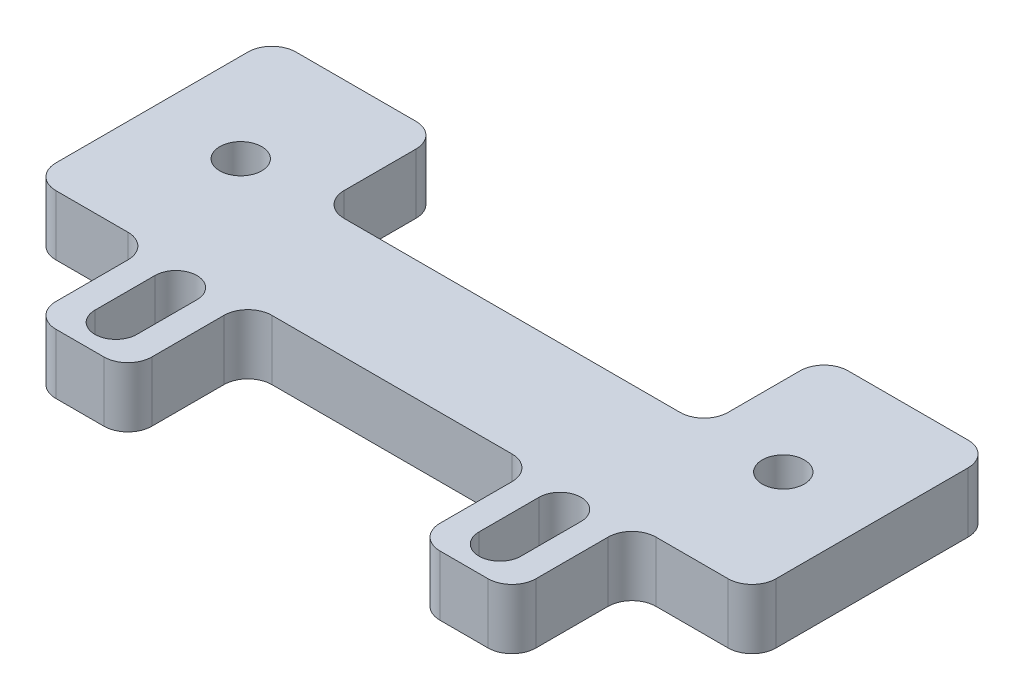
SolidWorks part; units mm, degrees
ref_plane "Front Plane" through (0, 0, 0) normal (0, 0, 1) x (1, 0, 0)
ref_plane "Top Plane" through (0, 0, 0) normal (0, 1, 0) x (1, 0, 0)
ref_plane "Right Plane" through (0, 0, 0) normal (1, 0, 0) x (0, 0, -1)
sketch "Sketch1" plane through (0, 0, 0) normal (0, 1, 0) x (1, 0, 0)
  line L0 (-38.1, 0) -> (-20.32, 0)
  line L1 (-38.1, 0) -> (-38.1, -25.4)
  line L2 (-38.1, -25.4) -> (-25.4, -25.4)
  line L3 (38.1, -25.4) -> (38.1, 0)
  line L4 (-38.1, -12.7) -> (38.1, -12.7) construction
  line L5 (0, -12.7) -> (0, -63.5) construction
  line L6 (-25.4, -25.4) -> (-25.4, -38.1)
  line L7 (-25.4, -38.1) -> (-15.24, -38.1)
  line L8 (25.4, -38.1) -> (25.4, -25.4)
  line L9 (25.4, -25.4) -> (38.1, -25.4)
  line L10 (-20.32, -38.1) -> (-20.32, 0) construction
  line L11 (20.32, -38.1) -> (20.32, 0) construction
  line L12 (-20.32, -27.94) -> (-20.32, -34.29) construction
  line L13 (-18.0975, -27.94) -> (-18.0975, -34.29)
  line L14 (-22.5425, -27.94) -> (-22.5425, -34.29)
  line L15 (20.32, -27.94) -> (20.32, -34.29) construction
  line L16 (18.0975, -27.94) -> (18.0975, -34.29)
  line L17 (22.5425, -27.94) -> (22.5425, -34.29)
  line L18 (-15.24, -38.1) -> (-15.24, -25.4)
  line L19 (-15.24, -25.4) -> (15.24, -25.4)
  line L20 (15.24, -25.4) -> (15.24, -38.1)
  line L21 (15.24, -38.1) -> (25.4, -38.1)
  line L22 (-20.32, 0) -> (-20.32, -12.7)
  line L23 (-20.32, -12.7) -> (20.32, -12.7)
  line L24 (20.32, -12.7) -> (20.32, 0)
  line L25 (20.32, 0) -> (38.1, 0)
  circle A0 centre (-28.702, -12.7) radius 2.2225
  circle A1 centre (28.702, -12.7) radius 2.2225
  arc A2 (-18.0975, -27.94) -> (-22.5425, -27.94) centre (-20.32, -27.94) ccw
  arc A3 (-22.5425, -34.29) -> (-18.0975, -34.29) centre (-20.32, -34.29) ccw
  arc A4 (18.0975, -27.94) -> (22.5425, -27.94) centre (20.32, -27.94) cw
  arc A5 (22.5425, -34.29) -> (18.0975, -34.29) centre (20.32, -34.29) cw
  point P4 (0, 0)
  point P24 (-20.32, -31.115)
  point P31 (20.32, -31.115)
  dimension "D3" = 4.445
  dimension "D4" = 57.404
  dimension "D7" = 2.2225
  dimension "D9" = 2.54
  dimension "D1" = 76.2
  dimension "D2" = 25.4
  dimension "D5" = 50.8
  dimension "D6" = 40.64
  dimension "D8" = 6.35
  dimension "D10" = 12.7
  dimension "D11" = 10.16
extrude "Boss-Extrude1" add sketch "Sketch1" along normal blind 6.35
fillet "Fillet1" radius 2.54 16 edges at (-38.1, 3.175, 0) (38.1, 3.175, 25.4) (25.4, 3.175, 25.4) (25.4, 3.175, 38.1) (15.24, 3.175, 38.1) (15.24, 3.175, 25.4) (-15.24, 3.175, 25.4) (-15.24, 3.175, 38.1) (-25.4, 3.175, 38.1) (-25.4, 3.175, 25.4) (-38.1, 3.175, 25.4) (38.1, 3.175, 0) (20.32, 3.175, 0) (20.32, 3.175, 12.7) (-20.32, 3.175, 12.7) (-20.32, 3.175, 0)
